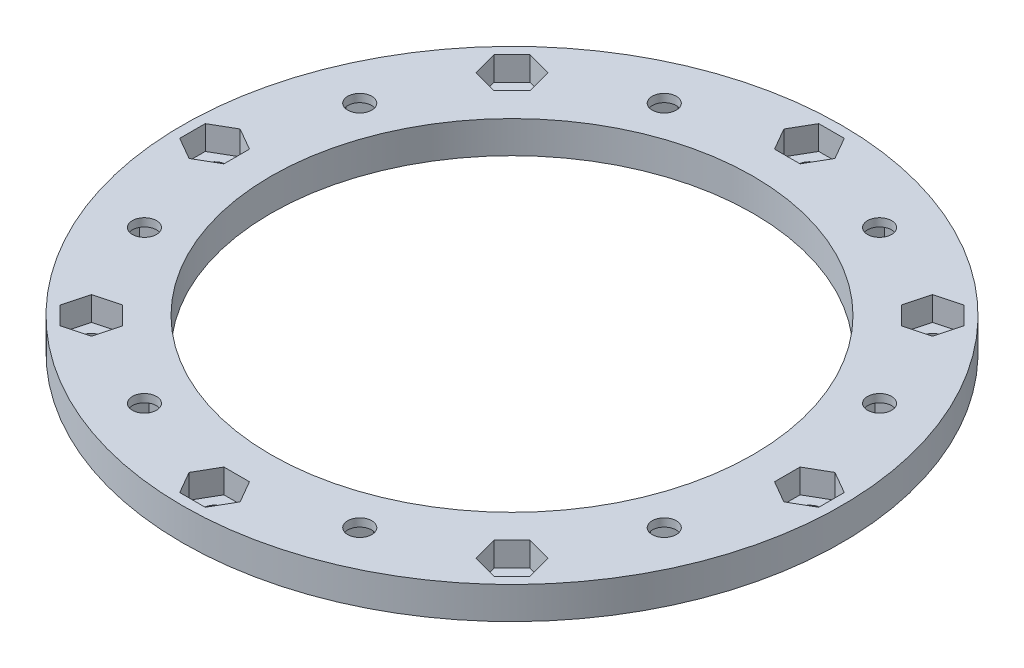
SolidWorks part; units mm, degrees
ref_plane "Front Plane" through (0, 0, 0) normal (0, 0, 1) x (1, 0, 0)
ref_plane "Top Plane" through (0, 0, 0) normal (0, 1, 0) x (1, 0, 0)
ref_plane "Right Plane" through (0, 0, 0) normal (1, 0, 0) x (0, 0, -1)
sketch "草图1" plane through (0, 0, 0) normal (0, 1, 0) x (1, 0, 0)
  circle A0 centre (0, 0) radius 37
  circle A2 centre (0, 37) radius 3
  circle A3 centre (0, 0) radius 35
  point P3 (0, 37)
  point P4 (-37, 0)
  point P5 (37, 0)
  dimension "D1" = 74
  dimension "D2" = 6
  dimension "D3" = 70
sketch "草图2" plane through (0, 0, 0) normal (0, 1, 0) x (1, 0, 0)
  circle A0 centre (0, 0) radius 41
  circle A1 centre (0, 0) radius 30
  dimension "D1" = 82
  dimension "D2" = 60
extrude "凸台-拉伸1" add sketch "草图2" along normal blind 4
sketch "草图3" plane through (0, 4, 0) normal (0, 1, 0) x (1, 0, 0)
  circle A0 centre (0, 0) radius 37 construction
  circle A1 centre (0, 37) radius 1.5
  dimension "D1" = 3
sketch "草图4" plane through (0, 4, 0) normal (0, 1, 0) x (1, 0, 0)
  line L1 (3.1754, 37) -> (1.5877, 39.75)
  line L2 (1.5877, 39.75) -> (-1.5877, 39.75)
  line L3 (-1.5877, 39.75) -> (-3.1754, 37)
  line L4 (-3.1754, 37) -> (-1.5877, 34.25)
  line L5 (-1.5877, 34.25) -> (1.5877, 34.25)
  line L6 (1.5877, 34.25) -> (3.1754, 37)
  circle A1 centre (0, 37) radius 2.75 construction
  dimension "D1" = 5.5
extrude "切除-拉伸1" cut sketch "草图3" against normal through all
extrude "切除-拉伸2" cut sketch "草图4" against normal blind 3
pattern_circular "阵列(圆周)1" count 24 over 360 about axis through (0, 4, 0) along (0, 1, 0) of "切除-拉伸2", "切除-拉伸1"
sketch "草图5" plane through (0, 0, 0) normal (0, -1, 0) x (1, 0, 0)
  line L0 (0, 35) -> (0, 0) construction
  line L1 (0, 0) -> (13.3939, 32.3358) construction
  circle A0 centre (13.3939, 32.3358) radius 1.5
  circle A1 centre (0, 0) radius 35 construction
  circle A2 centre (0, 0) radius 35 construction
  dimension "D1" = 3
  dimension "D2" = 22.5
sketch "草图6" plane through (0, 0, 0) normal (0, -1, 0) x (1, 0, 0)
  line L0 (0, 0) -> (13.3939, 32.3358) construction
  line L1 (12.1787, 29.4021) -> (15.327, 29.8165)
  line L2 (15.327, 29.8165) -> (16.5422, 32.7503)
  line L3 (16.5422, 32.7503) -> (14.6091, 35.2695)
  line L4 (14.6091, 35.2695) -> (11.4608, 34.855)
  line L5 (11.4608, 34.855) -> (10.2457, 31.9213)
  line L6 (10.2457, 31.9213) -> (12.1787, 29.4021)
  circle A2 centre (13.3939, 32.3358) radius 2.75 construction
  dimension "D1" = 5.5
extrude "切除-拉伸3" cut sketch "草图5" against normal through all
extrude "切除-拉伸4" cut sketch "草图6" against normal blind 3
pattern_circular "阵列(圆周)2" count 24 over 360 about axis through (0, 0, 0) along (0, 1, 0) of "切除-拉伸4", "切除-拉伸3"
